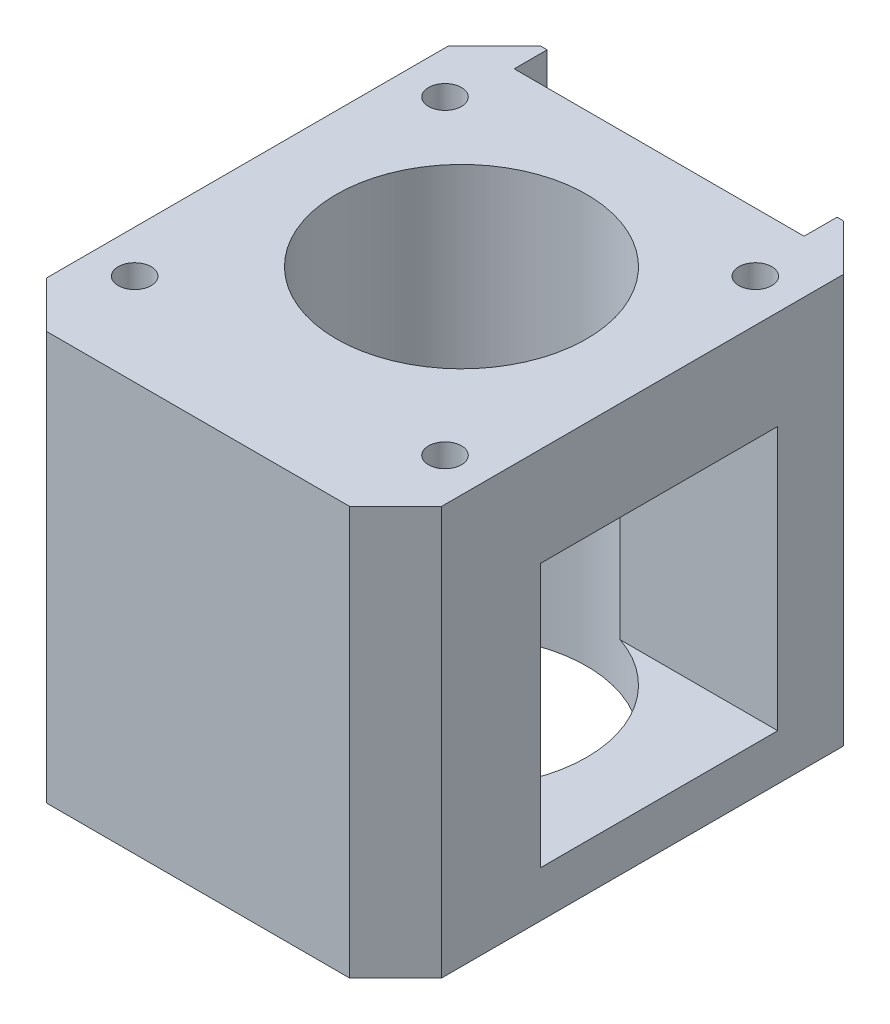
SolidWorks part; units mm, degrees
ref_plane "Front Plane" through (0, 0, 0) normal (0, 0, 1) x (1, 0, 0)
ref_plane "Top Plane" through (0, 0, 0) normal (0, 1, 0) x (1, 0, 0)
ref_plane "Right Plane" through (0, 0, 0) normal (1, 0, 0) x (0, 0, -1)
sketch "Sketch1" plane through (0, 0, 0) normal (0, 1, 0) x (1, 0, 0)
  line L1 (-30, 37.5) -> (30, 37.5)
  line L2 (-30, 37.5) -> (-30, -37.5)
  line L3 (-30, -37.5) -> (30, -37.5)
  line L4 (30, 37.5) -> (30, -37.5)
  line L5 (-30, 37.5) -> (30, -37.5) construction
  line L6 (-30, -37.5) -> (30, 37.5) construction
  point P0 (0, 0)
  dimension "D1" = 60
  dimension "D2" = 75
extrude "Boss-Extrude1" add sketch "Sketch1" along normal blind 62
sketch "Sketch2" plane through (0, 62, 0) normal (0, 1, 0) x (1, 0, 0)
  line L0 (30, 37.5) -> (-30, 37.5) construction
  line L1 (-22, 37.5) -> (22, 37.5)
  line L2 (-22, 37.5) -> (-22, 32.5)
  line L3 (-22, 32.5) -> (22, 32.5)
  line L4 (22, 37.5) -> (22, 32.5)
  line L5 (30, -37.5) -> (30, 37.5) construction
  circle A0 centre (0, 2.5) radius 19
  dimension "D5" = 38
  dimension "D1" = 5
  dimension "D2" = 44
  dimension "D3" = 8
  dimension "D4" = 30
extrude "Cut-Extrude1" cut sketch "Sketch2" against normal up to surface (62 mm away) up to face at (0, 0, 0)
sketch "Sketch3" plane through (30, 0, 0) normal (1, 0, 0) x (0, 0, -1)
  line L0 (-37.5, 62) -> (37.5, 62) construction
  line L1 (-15.5, 47) -> (20.5, 47)
  line L2 (-15.5, 47) -> (-15.5, 7)
  line L3 (-15.5, 7) -> (20.5, 7)
  line L4 (20.5, 47) -> (20.5, 7)
  line L5 (37.5, 62) -> (37.5, 0) construction
  dimension "D1" = 36
  dimension "D2" = 40
  dimension "D3" = 15
  dimension "D4" = 17
extrude "Cut-Extrude2" cut sketch "Sketch3" against normal up to surface (23.9172 mm away)
chamfer "Chamfer1" distance 7 angle 45 4 edges at (-30, 31, 37.5) (-30, 31, -37.5) (30, 31, -37.5) (30, 31, 37.5)
sketch "Sketch4" plane through (0, 0, -32.5) normal (0, 0, -1) x (-1, 0, 0)
  line L0 (-22, 0) -> (-22, 62) construction
  line L1 (22, 62) -> (-22, 62) construction
  circle A0 centre (-14, 53) radius 2.5
  circle A1 centre (14, 53) radius 2.5
  circle A2 centre (-14, 9) radius 2.5
  circle A3 centre (14, 9) radius 2.5
  dimension "D1" = 5
  dimension "D2" = 8
  dimension "D3" = 9
  dimension "D4" = 2
  dimension "D5" = 2
extrude "Cut-Extrude3" cut sketch "Sketch4" against normal blind 10
sketch "Sketch5" plane through (0, 62, 0) normal (0, 1, 0) x (1, 0, 0)
  circle A0 centre (-23.55, 23.55) radius 2.5
  circle A1 centre (23.55, 23.55) radius 2.5
  circle A2 centre (23.55, -23.55) radius 2.5
  circle A3 centre (-23.55, -23.55) radius 2.5
  point P12 (0, 0)
  dimension "D1" = 5
  dimension "D2" = 23.55
  dimension "D3" = 23.55
  dimension "D5" = 47.1
  dimension "D4" = 4
extrude "Cut-Extrude4" cut sketch "Sketch5" against normal blind 20
